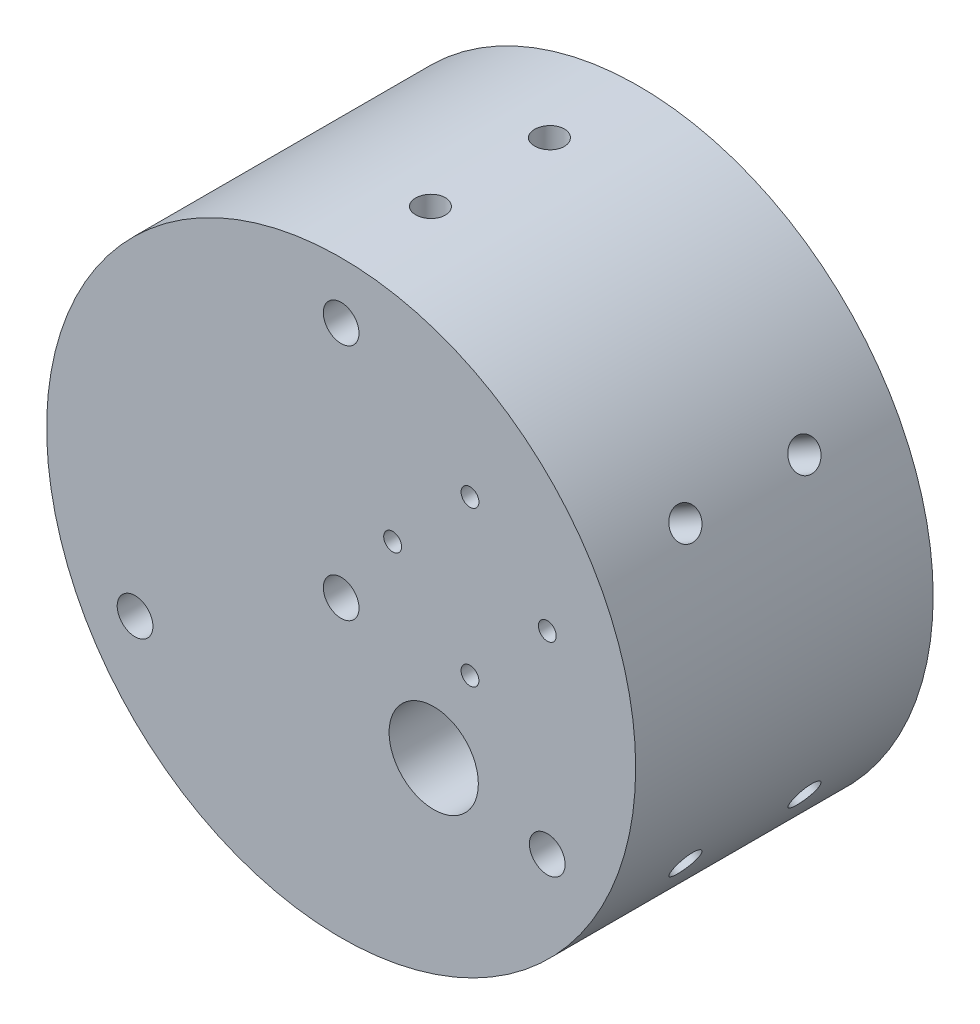
SolidWorks part; units mm, degrees
ref_plane "Front Plane" through (0, 0, 0) normal (0, 0, 1) x (1, 0, 0)
ref_plane "Top Plane" through (0, 0, 0) normal (0, 1, 0) x (1, 0, 0)
ref_plane "Right Plane" through (0, 0, 0) normal (1, 0, 0) x (0, 0, -1)
sketch "Sketch1" plane through (0, 0, 0) normal (0, 0, 1) x (1, 0, 0)
  circle A0 centre (0, 0) radius 49.5
  dimension "D1" = 99
extrude "Boss-Extrude1" add sketch "Sketch1" along normal blind 50
sketch "Sketch2" plane through (0, 0, 50) normal (0, 0, 1) x (1, 0, 0)
  line L0 (0, 40) -> (0, 0) construction
  line L1 (0, 0) -> (34.641, -20) construction
  line L2 (0, 0) -> (-34.641, -20) construction
  circle A0 centre (0, 0) radius 40 construction
  circle A1 centre (0, 40) radius 3
  circle A2 centre (34.641, -20) radius 3
  circle A3 centre (-34.641, -20) radius 3
  circle A4 centre (0, 0) radius 3
  point P11 (0, 0)
  dimension "D1" = 80
  dimension "D2" = 6
  dimension "D4" = 120
  dimension "D5" = 6
  dimension "D3" = 3
extrude "Cut-Extrude1" cut sketch "Sketch2" against normal through all
sketch "Sketch6" plane through (0, 0, 50) normal (0, 0, 1) x (1, 0, 0)
  line L0 (0, 0) -> (49.5, 0) construction
  line L1 (21.6506, 12.5) -> (0, 0) construction
  line L2 (21.6506, 12.5) -> (8.6506, 12.5) construction
  line L3 (8.6506, 12.5) -> (34.6506, 12.5) construction
  circle A0 centre (21.6506, 12.5) radius 15 construction
  circle A1 centre (0, 0) radius 49.5 construction
  circle A2 centre (21.6506, 12.5) radius 11 construction
  circle A3 centre (21.6506, 12.5) radius 9 construction
  circle A4 centre (21.6506, 25.5) radius 1.5
  circle A5 centre (21.6506, 12.5) radius 13 construction
  circle A6 centre (34.6506, 12.5) radius 1.5
  circle A7 centre (21.6506, -0.5) radius 1.5
  circle A8 centre (8.6506, 12.5) radius 1.5
  point P24 (21.6506, 12.5)
  dimension "D1" = 30
  dimension "D6" = 3
  dimension "D2" = 30
  dimension "D3" = 25
  dimension "D7" = 13
  dimension "D4" = 4
  dimension "D5" = 2
  dimension "D8" = 4
extrude "Cut-Extrude2" cut sketch "Sketch6" against normal blind 10
sketch "Sketch7" plane through (0, 0, 50) normal (0, 0, 1) x (1, 0, 0)
  line L0 (0, 0) -> (0, -20.1377) construction
  line L1 (0, 0) -> (15.5563, -15.5563) construction
  circle A0 centre (15.5563, -15.5563) radius 7.5
  dimension "D3" = 15
  dimension "D1" = 45
  dimension "D2" = 22
extrude "Cut-Extrude3" cut sketch "Sketch7" against normal through all
ref_plane "Plane1" through (0, -49.5, 0) normal (0, -1, 0) x (-1, 0, 0)
sketch "Sketch8" plane through (0, -49.5, 0) normal (0, -1, 0) x (-1, 0, 0)
  line L0 (-49.5, -50) -> (49.5, -50) construction
  circle A0 centre (0, -35) radius 2.5
  dimension "D1" = 5
  dimension "D2" = 15
extrude "Cut-Extrude4" cut sketch "Sketch8" against normal blind 10
pattern_circular "CirPattern1" count 6 over 360 about axis through (0, 0, 0) along (0, 0, 1) of "Cut-Extrude4"
sketch "Sketch9" plane through (0, -49.5, 0) normal (0, -1, 0) x (-1, 0, 0)
  circle A0 centre (0, -15) radius 2.5
  dimension "D1" = 5
  dimension "D2" = 15
extrude "Cut-Extrude5" cut sketch "Sketch9" against normal blind 10
pattern_circular "CirPattern2" count 6 over 360 about axis through (0, 0, 0) along (0, 0, 1) of "Cut-Extrude5"
